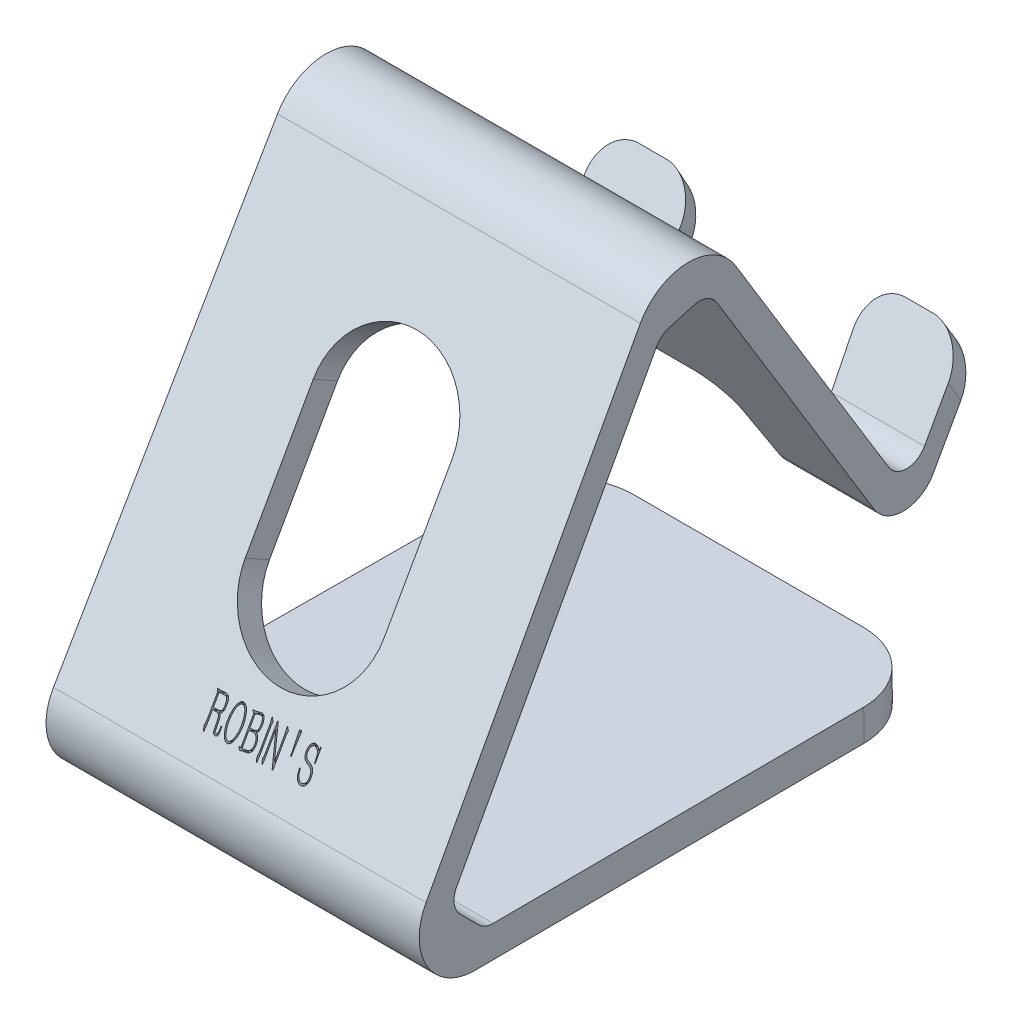
SolidWorks part; units mm, degrees
material "POM 乙缩醛共聚物"
ref_plane "前视基准面" through (0, 0, 0) normal (0, 0, 1) x (1, 0, 0)
ref_plane "上视基准面" through (0, 0, 0) normal (0, 1, 0) x (1, 0, 0)
ref_plane "右视基准面" through (0, 0, 0) normal (1, 0, 0) x (0, 0, -1)
other "Configuration Table"
sketch "草图1" plane through (0, 0, 0) normal (1, 0, 0) x (0, 0, -1)
  line L0 (0, 0) -> (80, 0)
  line L1 (29.7, 0) -> (-29.7, 0) construction
  line L2 (80, 0) -> (80, 4.5)
  line L3 (80, 4.5) -> (7.1206, 4.5)
  line L4 (7.1206, 4.5) -> (45.1332, 72.0778)
  line L5 (45.1332, 72.0778) -> (76.1332, 21.059)
  line L6 (76.1332, 21.059) -> (87.2505, 40.3148)
  line L7 (87.2505, 40.3148) -> (85.433, 43.3059)
  line L8 (85.433, 43.3059) -> (76.5962, 28)
  line L9 (76.5962, 28) -> (45, 80)
  line L10 (45, 80) -> (0, 0)
  point P5 (0, 0)
  point P14 (0, 0)
  point P15 (-46.6131, 87.8914)
  dimension "D1" = 80
  dimension "D2" = 80
  dimension "D3" = 4.5
  dimension "D4" = 4
  dimension "D5" = 31
  dimension "D6" = 4
  dimension "D7" = 3.5
  dimension "D8" = 28
  dimension "D9" = 45
  dimension "D10" = 60
  dimension "D11" = 15.5
extrude "凸台-拉伸1" add sketch "草图1" along normal mid plane 54
sketch "草图4" plane through (0, 0, 0) normal (0, 0.4903, 0.8716) x (1, 0, 0)
  line L0 (-27, 0) -> (-26, 91.7878)
  line L1 (-27, 91.7878) -> (-27, 0) construction
  line L2 (27, 91.7878) -> (-27, 91.7878) construction
  line L4 (-27, 91.7878) -> (-27, 0)
  line L5 (-27, 91.7878) -> (-26, 91.7878)
  line L6 (26, 91.7878) -> (27, 91.7878)
  line L9 (27, 0) -> (26, 91.7878)
  line L10 (27, 91.7878) -> (27, 0)
  dimension "D1" = 52
extrude "切除-拉伸1" cut sketch "草图4" against normal through all
sketch "草图7" plane through (0, 41.5417, -68.368) normal (0, 0.5193, -0.8546) x (-1, 0, 0)
  line L0 (-11.5, 0) -> (11.5, 0)
  line L1 (11.5, 0) -> (14, -25)
  line L2 (14, -25) -> (-14, -25)
  line L4 (-11.5, 0) -> (-14, -25)
  dimension "D1" = 23
  dimension "D2" = 28
  dimension "D3" = 25
extrude "切除-拉伸2" cut sketch "草图7" against normal up to next and the other way through all
fillet "圆角1" radius 10 2 edges at (-26.5513, 2.25, -80) (26.5513, 2.25, -80)
chamfer "倒角1" distance 8 angle 45 2 edges at (0, 72.0778, -45.1332) (0, 4.5, -7.1206)
fillet "圆角2" radius 8 2 edges at (0, 0, 0) (0, 80, -45)
fillet "圆角3" radius 3 2 edges at (-19.7048, 28, -76.5962) (19.7048, 28, -76.5962)
fillet "圆角4" radius 5 4 edges at (-26.1418, 41.8103, -86.3418) (-12.4104, 41.8103, -86.3418) (12.4104, 41.8103, -86.3418) (26.1418, 41.8103, -86.3418)
fillet "圆角5" radius 5 2 edges at (-20.0235, 21.059, -76.1332) (20.0235, 21.059, -76.1332)
sketch "草图8" plane through (0, 0, 0) normal (0, -1, 0) x (1, 0, 0)
  line L0 (0, -39.6856) -> (0, 39.6856) construction
  line L1 (16.6255, -80) -> (-16.6255, -80) construction
  circle A0 centre (-16.6255, -70) radius 7
  circle A1 centre (16.6255, -70) radius 7
  circle A2 centre (0, -25) radius 7
  ellipse E0 centre (-16.6255, -70) end of major axis (-26.626, -70) minor radius 10 (-26.6258, -70.0534) -> (-16.6255, -80) ccw construction
  ellipse E1 centre (16.6255, -70) end of major axis (6.6251, -70) minor radius 10 (16.6255, -80) -> (26.6258, -70.0534) ccw construction
  dimension "D1" = 55
extrude "凸台-拉伸2" add sketch "草图8" along normal blind 1
sketch "草图9" plane through (0, 0, 0) normal (0, 0.4903, 0.8716) x (1, 0, 0)
  line L0 (0, 35.6788) -> (0, 55.6788) construction
  line L1 (0, -40.2356) -> (0, 40.2356) construction
  line L2 (-10, 35.6788) -> (-10, 55.6788)
  line L3 (10, 35.6788) -> (10, 55.6788)
  line L4 (-26.851, 13.6788) -> (26.851, 13.6788) construction
  arc A0 (-10, 35.6788) -> (10, 35.6788) centre (0, 35.6788) ccw
  arc A1 (10, 55.6788) -> (-10, 55.6788) centre (0, 55.6788) ccw
  point P5 (0, 45.6788)
  dimension "D1" = 20
  dimension "D2" = 20
  dimension "D3" = 32
extrude "切除-拉伸3" cut sketch "草图9" against normal up to next
sketch "草图11" plane through (0, 0, 0) normal (0, 0.4903, 0.8716) x (1, 0, 0)
  text T0 "ROBIN'S" font "汉仪长仿宋体" height 5
extrude "切除-拉伸4" cut sketch "草图11" against normal blind 1
fillet "圆角6" radius 5 2 edges at (-11.5, 40.5031, -66.6588) (11.5, 40.5031, -66.6588)
sketch "草图12" plane through (0, 41.5417, -68.368) normal (0, 0.5193, -0.8546) x (-1, 0, 0)
  line L0 (0, 40.2356) -> (0, -40.2356) construction
  circle A0 centre (0, 16.0709) radius 13.2561
  circle A1 centre (0, 16.0709) radius 14.469
  text T0 "R" font "汉仪长仿宋体" height 20
extrude "切除-拉伸7" cut sketch "草图12" against normal blind 1 contours A0 | A1
sketch "草图13" plane through (0, 41.5417, -68.368) normal (0, 0.5193, -0.8546) x (-1, 0, 0)
  text T0 "R" font "汉仪长仿宋体" height 20
extrude "切除-拉伸8" cut sketch "草图13" against normal blind 1
fillet "圆角7" radius 3 4 edges at (0, 9.62, -10.0006) (0, 4.5, -15.1206) (0, 65.1052, -41.2111) (0, 67.0575, -48.1836)
